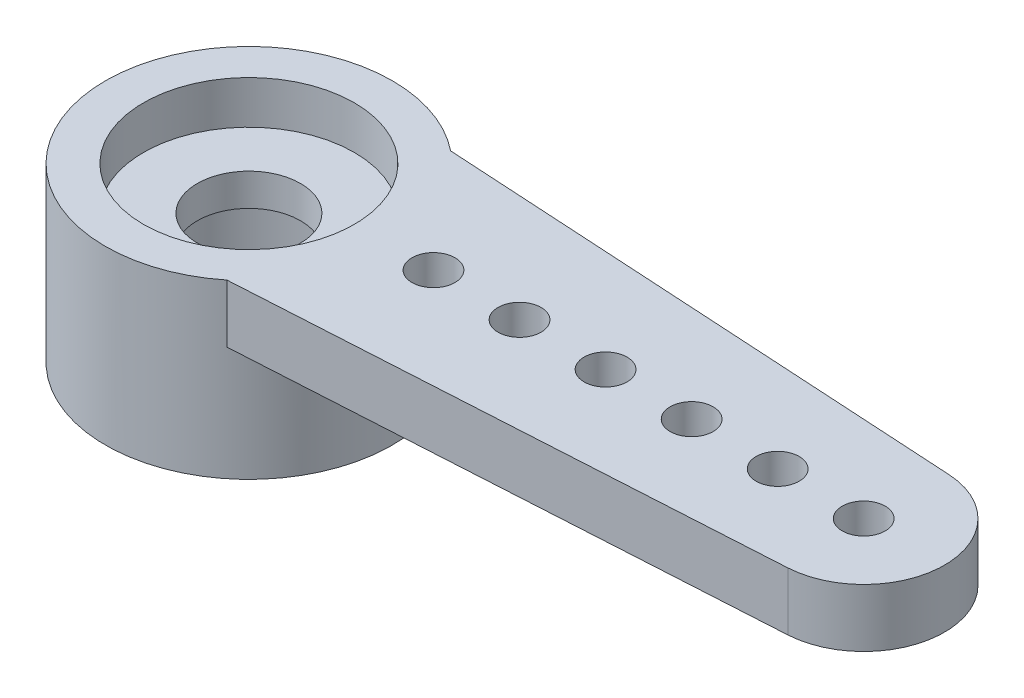
SolidWorks part; units mm, degrees
ref_plane "Front Plane" through (0, 0, 0) normal (0, 0, 1) x (1, 0, 0)
ref_plane "Top Plane" through (0, 0, 0) normal (0, 1, 0) x (1, 0, 0)
ref_plane "Right Plane" through (0, 0, 0) normal (1, 0, 0) x (0, 0, -1)
sketch "Sketch2" plane through (0, 0, 0) normal (0, 0, 1) x (1, 0, 0)
  line L0 (2.45, 0) -> (2.45, 2.25)
  line L1 (2.45, 2.25) -> (1.2, 2.25)
  line L2 (1.2, 2.25) -> (1.2, 3)
  line L3 (1.2, 3) -> (2.45, 3)
  line L4 (2.45, 3) -> (2.45, 4)
  line L5 (2.45, 4) -> (3.335, 4)
  line L6 (3.335, 4) -> (3.335, 0)
  line L7 (3.335, 0) -> (2.45, 0)
  line L8 (0, 0) -> (0, 4.1091) construction
  dimension "D1" = 2.25
  dimension "D2" = 4
  dimension "D3" = 1
  dimension "D4" = 2.45
  dimension "D5" = 3.335
  dimension "D6" = 1.2
  dimension "D7" = 2.45
revolve "Revolve1" add sketch "Sketch2" angle 360 about L8
sketch "Sketch3" plane through (0, 4, 0) normal (0, 1, 0) x (1, 0, 0)
  line L0 (2.0886, 2.6) -> (14.4004, 1.875)
  line L1 (14.4004, -1.875) -> (2.0886, -2.6)
  line L2 (0, 0) -> (14.29, 0) construction
  arc A0 (2.0886, -2.6) -> (2.0886, 2.6) centre (0, 0) ccw
  circle A1 centre (0, 0) radius 3.335 construction
  arc A2 (14.4004, 1.875) -> (14.4004, -1.875) centre (14.29, 0) cw
  circle A3 centre (14.29, 0) radius 0.5
  circle A4 centre (12.29, 0) radius 0.5
  circle A5 centre (10.29, 0) radius 0.5
  circle A6 centre (8.29, 0) radius 0.5
  circle A7 centre (6.29, 0) radius 0.5
  circle A8 centre (4.29, 0) radius 0.5
  dimension "D5" = 1
  dimension "D1" = 5.2
  dimension "D2" = 3.75
  dimension "D3" = 2.6
  dimension "D4" = 14.29
  dimension "D6" = 6
extrude "Boss-Extrude1" add sketch "Sketch3" against normal blind 1.35
